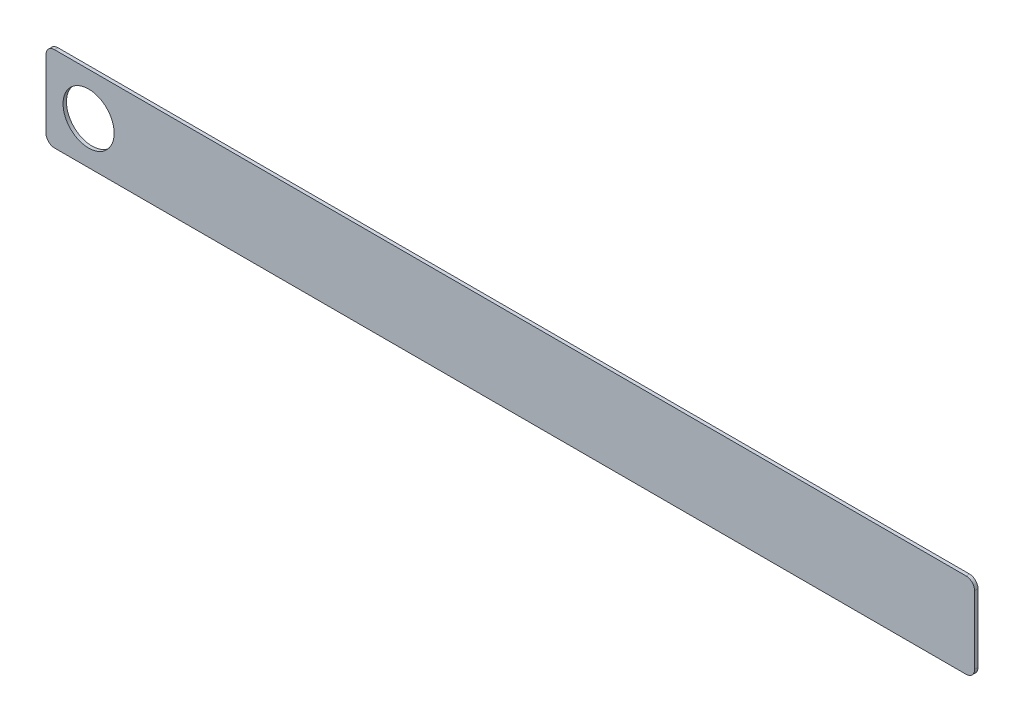
SolidWorks part; units mm, degrees
material "PE High Density"
ref_plane "Front Plane" through (0, 0, 0) normal (0, 0, 1) x (1, 0, 0)
ref_plane "Top Plane" through (0, 0, 0) normal (0, 1, 0) x (1, 0, 0)
ref_plane "Right Plane" through (0, 0, 0) normal (1, 0, 0) x (0, 0, -1)
sketch "Sketch1" plane through (0, 0, 0) normal (0, 0, 1) x (1, 0, 0)
  line L1 (-26.75, 2.5) -> (26.75, 2.5)
  line L2 (-27.25, 2) -> (-27.25, -2)
  line L3 (-26.75, -2.5) -> (26.75, -2.5)
  line L4 (27.25, 2) -> (27.25, -2)
  line L5 (-27.25, 2.5) -> (27.25, -2.5) construction
  line L6 (-27.25, -2.5) -> (27.25, 2.5) construction
  circle A0 centre (-24.75, 0) radius 1.5
  arc A1 (26.75, 2.5) -> (27.25, 2) centre (26.75, 2) cw
  arc A2 (26.75, -2.5) -> (27.25, -2) centre (26.75, -2) ccw
  arc A3 (-27.25, -2) -> (-26.75, -2.5) centre (-26.75, -2) ccw
  arc A4 (-26.75, 2.5) -> (-27.25, 2) centre (-26.75, 2) ccw
  point P0 (0, 0)
  dimension "D3" = 3
  dimension "D5" = 0.5
  dimension "D1" = 54.5
  dimension "D2" = 5
  dimension "D4" = 2.5
extrude "Boss-Extrude1" add sketch "Sketch1" along normal blind 0.2
scale "Scale6" scale about centroid uniform scaling yes scale factor 0.7
